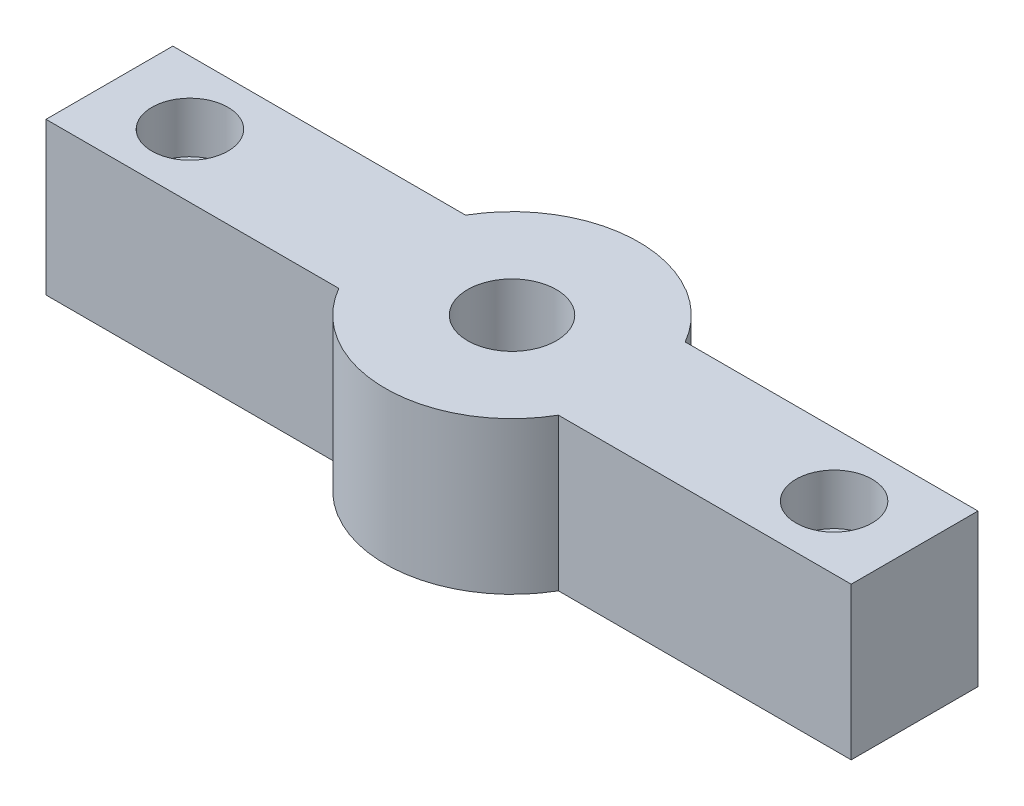
SolidWorks part; units mm, degrees
ref_plane "Front Plane" through (0, 0, 0) normal (0, 0, 1) x (1, 0, 0)
ref_plane "Top Plane" through (0, 0, 0) normal (0, 1, 0) x (1, 0, 0)
ref_plane "Right Plane" through (0, 0, 0) normal (1, 0, 0) x (0, 0, -1)
sketch "Sketch1" plane through (0, 0, 0) normal (0, 1, 0) x (1, 0, 0)
  line L0 (-15.875, 2.5) -> (-15.875, -2.5)
  line L1 (-15.875, -2.5) -> (-4.3301, -2.5)
  line L2 (15.875, -2.5) -> (15.875, 2.5)
  line L3 (15.875, 2.5) -> (4.3301, 2.5)
  line L4 (-15.875, 0) -> (15.875, 0) construction
  line L5 (-4.3301, 2.5) -> (-15.875, 2.5)
  line L6 (4.3301, -2.5) -> (15.875, -2.5)
  line L7 (0, 0) -> (0, 16.7972) construction
  arc A0 (-4.3301, -2.5) -> (4.3301, -2.5) centre (0, 0) ccw
  arc A1 (4.3301, 2.5) -> (-4.3301, 2.5) centre (0, 0) ccw
  circle A2 centre (-12.7, 0) radius 0.889
  circle A3 centre (0, 0) radius 1.75
  circle A4 centre (12.7, 0) radius 0.889
  dimension "D3" = 10
  dimension "D5" = 3.5
  dimension "D1" = 5
  dimension "D2" = 31.75
  dimension "D4" = 12.7
extrude "Boss-Extrude1" add sketch "Sketch1" along normal blind 6
sketch "Sketch2" plane through (0, 6, 0) normal (0, 1, 0) x (1, 0, 0)
  circle A0 centre (-12.7, 0) radius 1.5
  circle A1 centre (12.7, 0) radius 1.5
extrude "Cut-Extrude1" cut sketch "Sketch2" against normal blind 2
